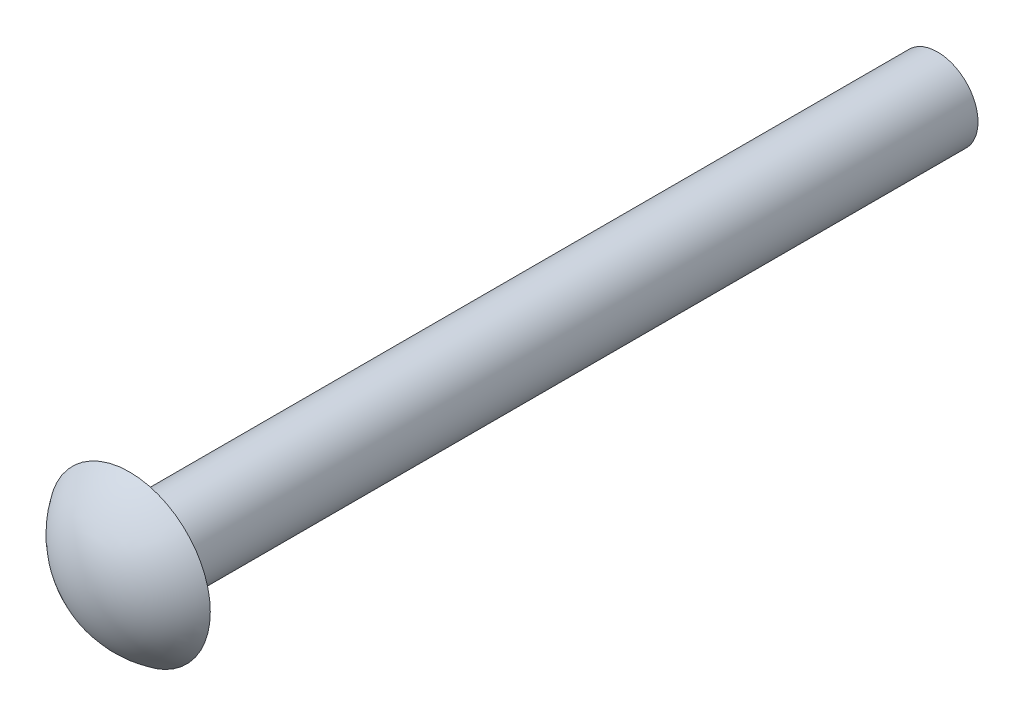
SolidWorks part; units mm, degrees
ref_plane "Front Plane" through (0, 0, 0) normal (0, 0, 1) x (1, 0, 0)
ref_plane "Top Plane" through (0, 0, 0) normal (0, 1, 0) x (1, 0, 0)
ref_plane "Right Plane" through (0, 0, 0) normal (1, 0, 0) x (0, 0, -1)
sketch "Sketch1" plane through (0, 0, 0) normal (1, 0, 0) x (0, 0, -1)
  line L0 (0, 0) -> (0, 1.27)
  line L1 (-0.6816, 0) -> (0, 0)
  arc A0 (0, 1.27) -> (-0.6816, 0) centre (0.8424, 0) ccw
  dimension "D1" = 1.27
  dimension "D2" = 1.524
revolve "Revolve1" add sketch "Sketch1" angle 360 about L1
sketch "Sketch2" plane through (0, 0, 0) normal (0, 0, -1) x (-1, 0, 0)
  circle A0 centre (0, 0) radius 0.635
  dimension "D1" = 1.27
extrude "Boss-Extrude1" add sketch "Sketch2" along normal blind 12.7
ref_plane "Plane1" through (0, 0, -10.16) normal (0, 0, -1) x (-1, 0, 0)
ref_plane "Plane2" through (0, 0, -8.128) normal (0, 0, -1) x (-1, 0, 0)
